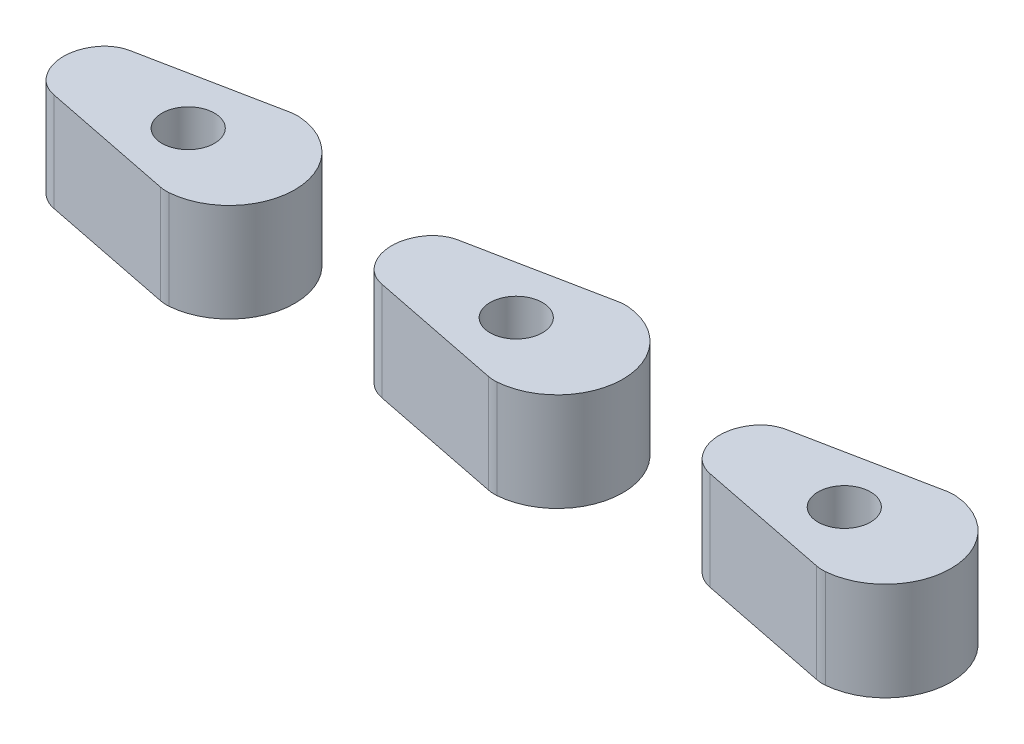
SolidWorks part; units mm, degrees
ref_plane "Front Plane" through (0, 0, 0) normal (0, 0, 1) x (1, 0, 0)
ref_plane "Top Plane" through (0, 0, 0) normal (0, 1, 0) x (1, 0, 0)
ref_plane "Right Plane" through (0, 0, 0) normal (1, 0, 0) x (0, 0, -1)
sketch "Sketch1" plane through (0, 0, 0) normal (0, 1, 0) x (1, 0, 0)
  line L0 (-0.1139, 1.9772) -> (-1.25, 1.7502)
  line L1 (-0.1139, -1.9772) -> (-1.25, -1.7502)
  line L2 (-1.25, 0) -> (-6.2818, 0) construction
  line L4 (-1.25, -1.7502) -> (-4.1832, -1.1642)
  line L5 (-1.25, 1.7502) -> (-4.1832, 1.1642)
  circle A1 centre (-1.25, 0) radius 0.8
  arc A2 (0.1641, 1.9933) -> (0.1641, -1.9933) centre (0, 0) cw
  arc A3 (-0.1139, -1.9772) -> (0.1641, -1.9933) centre (0.0821, -0.9966) ccw
  arc A4 (-4.7783, 0.7954) -> (-4.7783, -0.7954) centre (-3.75, 0) ccw
  arc A5 (0.1641, 1.9933) -> (-0.1139, 1.9772) centre (0.0821, 0.9966) ccw
  arc A6 (-4.1832, 1.1642) -> (-4.7783, 0.7954) centre (-3.9873, 0.1835) ccw
  arc A7 (-4.1832, -1.1642) -> (-4.7783, -0.7954) centre (-3.9873, -0.1835) cw
  circle A8 centre (-3, 0) radius 0.3
  circle A9 centre (0.5, 0) radius 0.3
  point P12 (-3, 0)
  point P20 (0.5, 0)
extrude "Boss-Extrude1" add sketch "Sketch1" along normal blind 3 contours L2 A9 | A9 L2 | A2 L2 A9 A1 A8 A4 A7 L4 L1 A3 | L2 A2 A5 L0 L5 A6 A4 A8 A1 A9 | L2 A8 | A8 L2
pattern_linear "LPattern1" count 3 spacing 10 along (-1, 0, 0) of bodies 184
